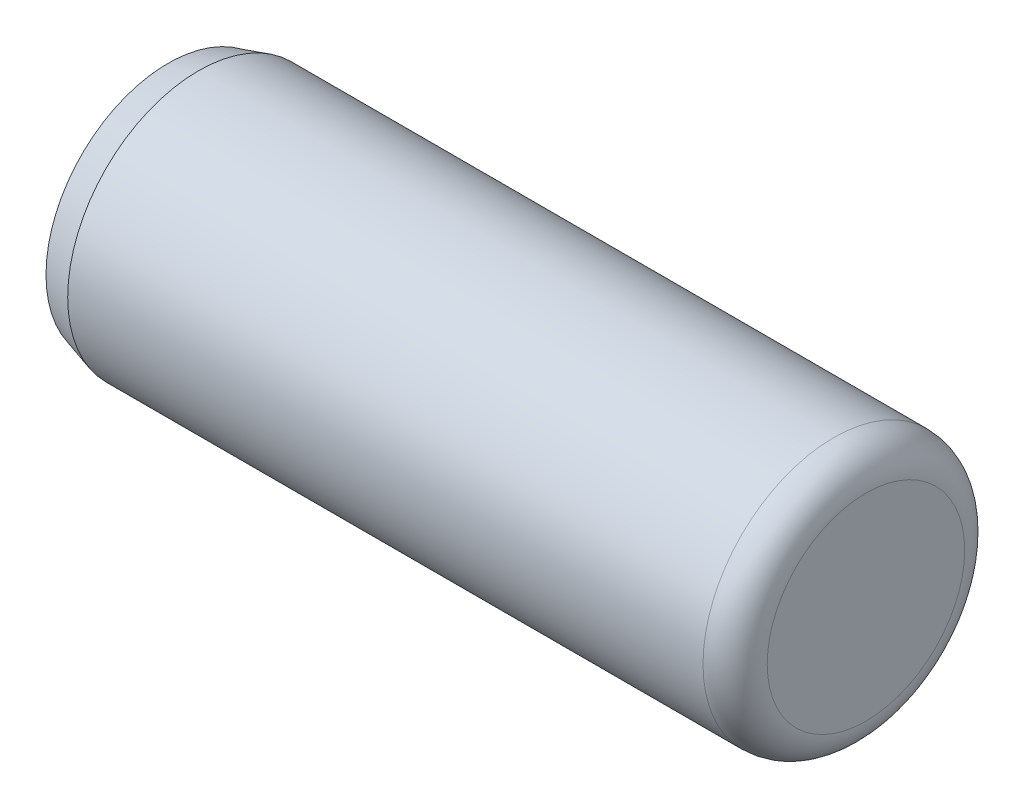
SolidWorks part; units mm, degrees
ref_plane "Front" through (0, 0, 0) normal (0, 0, 1) x (1, 0, 0)
ref_plane "Top" through (0, 0, 0) normal (0, 1, 0) x (1, 0, 0)
ref_plane "Right" through (0, 0, 0) normal (1, 0, 0) x (0, 0, -1)
sketch "Sketch1" plane through (0, 0, 0) normal (1, 0, 0) x (0, 0, -1)
  circle A0 centre (0, 0) radius 2.3813 construction
  point P3 (0, 2.3813)
  dimension "Diameter" = 4.7625
sketch "Sketch2" plane through (0, 0, 0) normal (0, 0, 1) x (1, 0, 0)
  line L0 (-6.35, 0) -> (6.35, 0) construction
  line L1 (6.35, 1.7971) -> (6.35, -0.6481) construction
  line L2 (-6.35, 2.2225) -> (-6.35, -2.2225) construction
  line L3 (-6.35, 2.2225) -> (-6.35, 2.3813) construction
  line L4 (-6.35, -2.2225) -> (-6.35, -2.3813) construction
  line L5 (-6.35, 2.2225) -> (-5.7964, 2.3813) construction
  line L6 (-5.7964, 2.3813) -> (5.7658, 2.3813) construction
  arc A0 (5.7658, 2.3813) -> (6.35, 1.7971) centre (5.7658, 1.7971) cw construction
  point P6 (-1.5875, 0)
  point P8 (1.5875, 0)
  point P23 (4.7752, 2.3812)
  dimension "Crown Radius" = 0.5842
  dimension "Length" = 12.7
  dimension "D1" = 4.7625
  dimension "D2" = 4.7625
  dimension "Point Diameter" = 4.445
  dimension "D3" = 16
  dimension "Crown Height" = 1.5748
sketch "Sketch3" plane through (0, 0, 0) normal (0, 0, 1) x (1, 0, 0)
  line L0 (6.35, 1.7971) -> (6.35, -0.6481) construction
  line L1 (-5.7964, 2.3813) -> (5.7658, 2.3813) construction
  line L2 (-6.35, 2.2225) -> (-5.7964, 2.3813) construction
  line L3 (-6.35, 2.2225) -> (-6.35, -2.2225) construction
  line L4 (-6.35, 0) -> (6.35, 0) construction
  line L5 (6.35, 1.7971) -> (6.35, 0)
  line L6 (-5.7964, 2.3813) -> (5.7658, 2.3813)
  line L7 (-6.35, 2.2225) -> (-5.7964, 2.3813)
  line L8 (-6.35, 2.2225) -> (-6.35, 0)
  line L9 (-6.35, 0) -> (6.35, 0)
  arc A0 (6.35, 1.7971) -> (5.7658, 2.3813) centre (5.7658, 1.7971) ccw construction
  arc A1 (6.35, 1.7971) -> (5.7658, 2.3813) centre (5.7658, 1.7971) ccw
revolve "Revolve1" add sketch "Sketch3" angle 360 about L0
equation "\"D1@Sketch2\" = \"Diameter@Sketch1\""
equation "\"D2@Sketch2\" = \"Diameter@Sketch1\""
